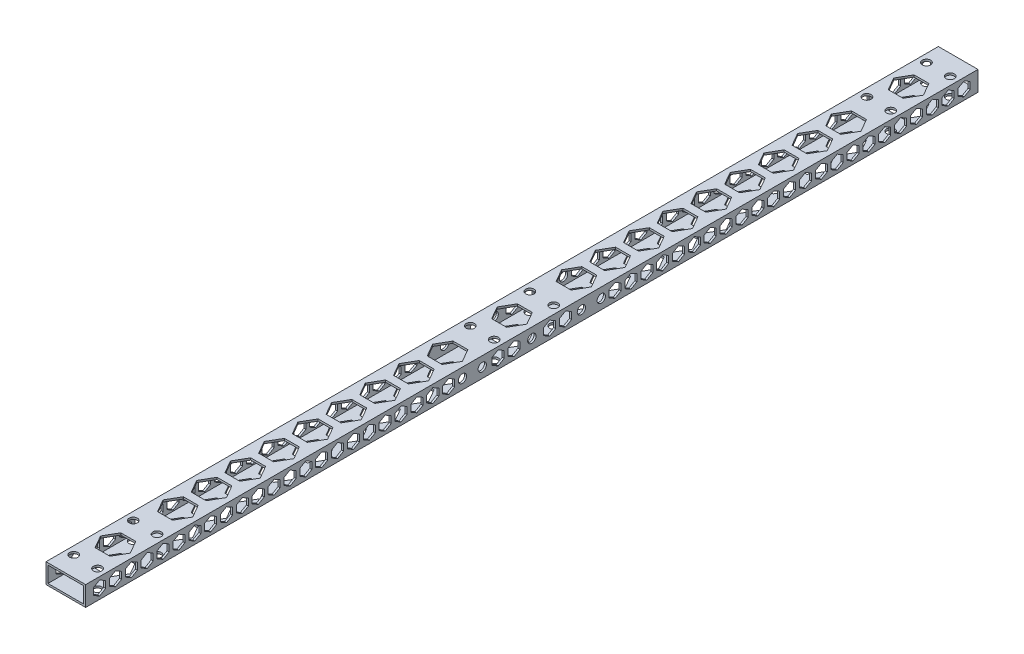
SolidWorks part; units mm, degrees
ref_plane "前视基准面" through (0, 0, 0) normal (0, 0, 1) x (1, 0, 0)
ref_plane "上视基准面" through (0, 0, 0) normal (0, 1, 0) x (1, 0, 0)
ref_plane "右视基准面" through (0, 0, 0) normal (1, 0, 0) x (0, 0, -1)
other "Configuration Table"
sketch "草图1" plane through (0, 0, 0) normal (0, 0, 1) x (1, 0, 0)
  line L1 (0, 0) -> (20, 0)
  line L2 (0, 0) -> (0, -10)
  line L3 (0, -10) -> (20, -10)
  line L4 (20, 0) -> (20, -10)
  dimension "D1" = 10
  dimension "D2" = 20
extrude "拉伸-薄壁1" add sketch "草图1" along normal blind 450 thin
sketch "草图2" plane through (0, 0, 0) normal (0, 1, 0) x (1, 0, 0)
  line L0 (20, -225) -> (0, -225) construction
  line L1 (20, -450) -> (20, 0) construction
  line L2 (0, -450) -> (0, 0) construction
  line L3 (10, 0) -> (10, -450) construction
  line L4 (20, 0) -> (0, 0) construction
  line L5 (20, -450) -> (0, -450) construction
  line L6 (20, -25) -> (0, -25) construction
  line L7 (20, -425) -> (0, -425) construction
  line L8 (13.75, -67) -> (6.25, -67)
  line L9 (13.75, -50) -> (6.25, -50)
  line L10 (6.25, -50) -> (2.5, -56.4952)
  line L11 (2.5, -56.4952) -> (6.25, -62.9904)
  line L12 (6.25, -62.9904) -> (13.75, -62.9904)
  line L13 (13.75, -62.9904) -> (17.5, -56.4952)
  line L14 (17.5, -56.4952) -> (13.75, -50)
  line L15 (17.5, -73.4952) -> (13.75, -67)
  line L16 (13.75, -79.9904) -> (17.5, -73.4952)
  line L17 (6.25, -79.9904) -> (13.75, -79.9904)
  line L18 (2.5, -73.4952) -> (6.25, -79.9904)
  line L19 (6.25, -67) -> (2.5, -73.4952)
  line L20 (13.75, -84) -> (6.25, -84)
  line L21 (17.5, -90.4952) -> (13.75, -84)
  line L22 (13.75, -96.9904) -> (17.5, -90.4952)
  line L23 (6.25, -96.9904) -> (13.75, -96.9904)
  line L24 (2.5, -90.4952) -> (6.25, -96.9904)
  line L25 (6.25, -84) -> (2.5, -90.4952)
  line L26 (13.75, -101) -> (6.25, -101)
  line L27 (17.5, -107.4952) -> (13.75, -101)
  line L28 (13.75, -113.9904) -> (17.5, -107.4952)
  line L29 (6.25, -113.9904) -> (13.75, -113.9904)
  line L30 (2.5, -107.4952) -> (6.25, -113.9904)
  line L31 (6.25, -101) -> (2.5, -107.4952)
  line L32 (13.75, -118) -> (6.25, -118)
  line L33 (17.5, -124.4952) -> (13.75, -118)
  line L34 (13.75, -130.9904) -> (17.5, -124.4952)
  line L35 (6.25, -130.9904) -> (13.75, -130.9904)
  line L36 (2.5, -124.4952) -> (6.25, -130.9904)
  line L37 (6.25, -118) -> (2.5, -124.4952)
  line L38 (13.75, -135) -> (6.25, -135)
  line L39 (17.5, -141.4952) -> (13.75, -135)
  line L40 (13.75, -147.9904) -> (17.5, -141.4952)
  line L41 (6.25, -147.9904) -> (13.75, -147.9904)
  line L42 (2.5, -141.4952) -> (6.25, -147.9904)
  line L43 (6.25, -135) -> (2.5, -141.4952)
  line L44 (13.75, -152) -> (6.25, -152)
  line L45 (17.5, -158.4952) -> (13.75, -152)
  line L46 (13.75, -164.9904) -> (17.5, -158.4952)
  line L47 (6.25, -164.9904) -> (13.75, -164.9904)
  line L48 (2.5, -158.4952) -> (6.25, -164.9904)
  line L49 (6.25, -152) -> (2.5, -158.4952)
  line L50 (13.75, -169) -> (6.25, -169)
  line L51 (17.5, -175.4952) -> (13.75, -169)
  line L52 (13.75, -181.9904) -> (17.5, -175.4952)
  line L53 (6.25, -181.9904) -> (13.75, -181.9904)
  line L54 (2.5, -175.4952) -> (6.25, -181.9904)
  line L55 (6.25, -169) -> (2.5, -175.4952)
  line L56 (13.75, -186) -> (6.25, -186)
  line L57 (17.5, -192.4952) -> (13.75, -186)
  line L58 (13.75, -198.9904) -> (17.5, -192.4952)
  line L59 (6.25, -198.9904) -> (13.75, -198.9904)
  line L60 (2.5, -192.4952) -> (6.25, -198.9904)
  line L61 (6.25, -186) -> (2.5, -192.4952)
  line L62 (6.25, -251.0096) -> (13.75, -251.0096)
  line L63 (13.75, -251.0096) -> (17.5, -257.5048)
  line L64 (2.5, -257.5048) -> (6.25, -251.0096)
  line L65 (6.25, -264) -> (2.5, -257.5048)
  line L66 (17.5, -257.5048) -> (13.75, -264)
  line L67 (13.75, -264) -> (6.25, -264)
  line L68 (6.25, -281) -> (2.5, -274.5048)
  line L69 (2.5, -274.5048) -> (6.25, -268.0096)
  line L70 (6.25, -268.0096) -> (13.75, -268.0096)
  line L71 (13.75, -268.0096) -> (17.5, -274.5048)
  line L72 (17.5, -274.5048) -> (13.75, -281)
  line L73 (13.75, -281) -> (6.25, -281)
  line L74 (6.25, -298) -> (2.5, -291.5048)
  line L75 (2.5, -291.5048) -> (6.25, -285.0096)
  line L76 (6.25, -285.0096) -> (13.75, -285.0096)
  line L77 (13.75, -285.0096) -> (17.5, -291.5048)
  line L78 (17.5, -291.5048) -> (13.75, -298)
  line L79 (13.75, -298) -> (6.25, -298)
  line L80 (6.25, -315) -> (2.5, -308.5048)
  line L81 (2.5, -308.5048) -> (6.25, -302.0096)
  line L82 (6.25, -302.0096) -> (13.75, -302.0096)
  line L83 (13.75, -302.0096) -> (17.5, -308.5048)
  line L84 (17.5, -308.5048) -> (13.75, -315)
  line L85 (13.75, -315) -> (6.25, -315)
  line L86 (6.25, -332) -> (2.5, -325.5048)
  line L87 (2.5, -325.5048) -> (6.25, -319.0096)
  line L88 (6.25, -319.0096) -> (13.75, -319.0096)
  line L89 (13.75, -319.0096) -> (17.5, -325.5048)
  line L90 (17.5, -325.5048) -> (13.75, -332)
  line L91 (13.75, -332) -> (6.25, -332)
  line L92 (6.25, -349) -> (2.5, -342.5048)
  line L93 (2.5, -342.5048) -> (6.25, -336.0096)
  line L94 (6.25, -336.0096) -> (13.75, -336.0096)
  line L95 (13.75, -336.0096) -> (17.5, -342.5048)
  line L96 (17.5, -342.5048) -> (13.75, -349)
  line L97 (13.75, -349) -> (6.25, -349)
  line L98 (6.25, -366) -> (2.5, -359.5048)
  line L99 (2.5, -359.5048) -> (6.25, -353.0096)
  line L100 (6.25, -353.0096) -> (13.75, -353.0096)
  line L101 (13.75, -353.0096) -> (17.5, -359.5048)
  line L102 (17.5, -359.5048) -> (13.75, -366)
  line L103 (13.75, -366) -> (6.25, -366)
  line L104 (6.25, -383) -> (2.5, -376.5048)
  line L105 (2.5, -376.5048) -> (6.25, -370.0096)
  line L106 (6.25, -370.0096) -> (13.75, -370.0096)
  line L107 (13.75, -370.0096) -> (17.5, -376.5048)
  line L108 (17.5, -376.5048) -> (13.75, -383)
  line L109 (17.5, -393.5048) -> (13.75, -400)
  line L110 (13.75, -387.0096) -> (17.5, -393.5048)
  line L111 (6.25, -387.0096) -> (13.75, -387.0096)
  line L112 (2.5, -393.5048) -> (6.25, -387.0096)
  line L113 (6.25, -400) -> (2.5, -393.5048)
  line L114 (13.75, -400) -> (6.25, -400)
  line L115 (13.75, -383) -> (6.25, -383)
  line L116 (20, -25) -> (0, -25) construction
  line L117 (2.5, -425) -> (6.25, -431.4952)
  line L118 (6.25, -431.4952) -> (13.75, -431.4952)
  line L119 (13.75, -431.4952) -> (17.5, -425)
  line L120 (17.5, -425) -> (13.75, -418.5048)
  line L121 (13.75, -418.5048) -> (6.25, -418.5048)
  line L122 (6.25, -418.5048) -> (2.5, -425)
  line L123 (6.25, -31.4952) -> (2.5, -25)
  line L124 (13.75, -31.4952) -> (6.25, -31.4952)
  line L125 (17.5, -25) -> (13.75, -31.4952)
  line L126 (13.75, -18.5048) -> (17.5, -25)
  line L127 (6.25, -18.5048) -> (13.75, -18.5048)
  line L128 (2.5, -25) -> (6.25, -18.5048)
  line L130 (2.5, -225) -> (6.25, -231.4952)
  line L131 (6.25, -231.4952) -> (13.75, -231.4952)
  line L132 (13.75, -231.4952) -> (17.5, -225)
  line L133 (17.5, -225) -> (13.75, -218.5048)
  line L134 (13.75, -218.5048) -> (6.25, -218.5048)
  line L135 (6.25, -218.5048) -> (2.5, -225)
  circle A0 centre (4, -210) radius 2.1
  circle A1 centre (16, -210) radius 2.1
  circle A2 centre (16, -240) radius 2.1
  circle A3 centre (4, -240) radius 2.1
  circle A4 centre (4, -10) radius 2.1
  circle A5 centre (16, -10) radius 2.1
  circle A6 centre (16, -40) radius 2.1
  circle A7 centre (4, -40) radius 2.1
  circle A8 centre (4, -410) radius 2.1
  circle A9 centre (16, -410) radius 2.1
  circle A10 centre (16, -440) radius 2.1
  circle A11 centre (4, -440) radius 2.1
  circle A12 centre (10, -56.4952) radius 6.4952 construction
  circle A13 centre (10, -393.5048) radius 6.4952 construction
  circle A14 centre (10, -425) radius 6.4952 construction
  circle A15 centre (10, -25) radius 6.4952 construction
  circle A16 centre (10, -225) radius 6.4952 construction
  point P153 (2.5, -225)
  dimension "D1" = 4.2
  dimension "D5" = 4.2
  dimension "D2" = 6
  dimension "D3" = 15
  dimension "D4" = 200
  dimension "D6" = 6
  dimension "D7" = 15
  dimension "D8" = 7.5
  dimension "D9" = 10
  dimension "D11" = 17
  dimension "D12" = 7.5
  dimension "D13" = 7.5
  dimension "D10" = 9
extrude "切除-拉伸1" cut sketch "草图2" against normal through all
sketch "草图3" plane through (20, 0, 0) normal (1, 0, 0) x (0, 0, -1)
  line L0 (-225, 0) -> (-225, -10) construction
  line L1 (-450, 0) -> (0, 0) construction
  line L2 (-450, -10) -> (0, -10) construction
  line L3 (-225, -5) -> (-450, -5) construction
  line L4 (-450, -10) -> (-450, 0) construction
  line L5 (-434.9689, -1.5) -> (-438, -3.25)
  line L6 (-442.9689, -1.5) -> (-446, -3.25)
  line L7 (-446, -3.25) -> (-446, -6.75)
  line L8 (-446, -6.75) -> (-442.9689, -8.5)
  line L9 (-442.9689, -8.5) -> (-439.9378, -6.75)
  line L10 (-439.9378, -6.75) -> (-439.9378, -3.25)
  line L11 (-439.9378, -3.25) -> (-442.9689, -1.5)
  line L12 (-431.9378, -3.25) -> (-434.9689, -1.5)
  line L13 (-438, -3.25) -> (-438, -6.75)
  line L14 (-431.9378, -6.75) -> (-431.9378, -3.25)
  line L15 (-434.9689, -8.5) -> (-431.9378, -6.75)
  line L16 (-438, -6.75) -> (-434.9689, -8.5)
  line L17 (-426.9689, -1.5) -> (-430, -3.25)
  line L18 (-423.9378, -3.25) -> (-426.9689, -1.5)
  line L19 (-430, -3.25) -> (-430, -6.75)
  line L20 (-423.9378, -6.75) -> (-423.9378, -3.25)
  line L21 (-426.9689, -8.5) -> (-423.9378, -6.75)
  line L22 (-430, -6.75) -> (-426.9689, -8.5)
  line L23 (-418.9689, -1.5) -> (-422, -3.25)
  line L24 (-415.9378, -3.25) -> (-418.9689, -1.5)
  line L25 (-422, -3.25) -> (-422, -6.75)
  line L26 (-415.9378, -6.75) -> (-415.9378, -3.25)
  line L27 (-418.9689, -8.5) -> (-415.9378, -6.75)
  line L28 (-422, -6.75) -> (-418.9689, -8.5)
  line L29 (-410.9689, -1.5) -> (-414, -3.25)
  line L30 (-407.9378, -3.25) -> (-410.9689, -1.5)
  line L31 (-414, -3.25) -> (-414, -6.75)
  line L32 (-407.9378, -6.75) -> (-407.9378, -3.25)
  line L33 (-410.9689, -8.5) -> (-407.9378, -6.75)
  line L34 (-414, -6.75) -> (-410.9689, -8.5)
  line L35 (-402.9689, -1.5) -> (-406, -3.25)
  line L36 (-399.9378, -3.25) -> (-402.9689, -1.5)
  line L37 (-406, -3.25) -> (-406, -6.75)
  line L38 (-399.9378, -6.75) -> (-399.9378, -3.25)
  line L39 (-402.9689, -8.5) -> (-399.9378, -6.75)
  line L40 (-406, -6.75) -> (-402.9689, -8.5)
  line L41 (-394.9689, -1.5) -> (-398, -3.25)
  line L42 (-391.9378, -3.25) -> (-394.9689, -1.5)
  line L43 (-398, -3.25) -> (-398, -6.75)
  line L44 (-391.9378, -6.75) -> (-391.9378, -3.25)
  line L45 (-394.9689, -8.5) -> (-391.9378, -6.75)
  line L46 (-398, -6.75) -> (-394.9689, -8.5)
  line L47 (-386.9689, -1.5) -> (-390, -3.25)
  line L48 (-383.9378, -3.25) -> (-386.9689, -1.5)
  line L49 (-390, -3.25) -> (-390, -6.75)
  line L50 (-383.9378, -6.75) -> (-383.9378, -3.25)
  line L51 (-386.9689, -8.5) -> (-383.9378, -6.75)
  line L52 (-390, -6.75) -> (-386.9689, -8.5)
  line L53 (-378.9689, -1.5) -> (-382, -3.25)
  line L54 (-375.9378, -3.25) -> (-378.9689, -1.5)
  line L55 (-382, -3.25) -> (-382, -6.75)
  line L56 (-375.9378, -6.75) -> (-375.9378, -3.25)
  line L57 (-378.9689, -8.5) -> (-375.9378, -6.75)
  line L58 (-382, -6.75) -> (-378.9689, -8.5)
  line L59 (-370.9689, -1.5) -> (-374, -3.25)
  line L60 (-367.9378, -3.25) -> (-370.9689, -1.5)
  line L61 (-374, -3.25) -> (-374, -6.75)
  line L62 (-367.9378, -6.75) -> (-367.9378, -3.25)
  line L63 (-370.9689, -8.5) -> (-367.9378, -6.75)
  line L64 (-374, -6.75) -> (-370.9689, -8.5)
  line L65 (-362.9689, -1.5) -> (-366, -3.25)
  line L66 (-359.9378, -3.25) -> (-362.9689, -1.5)
  line L67 (-366, -3.25) -> (-366, -6.75)
  line L68 (-359.9378, -6.75) -> (-359.9378, -3.25)
  line L69 (-362.9689, -8.5) -> (-359.9378, -6.75)
  line L70 (-366, -6.75) -> (-362.9689, -8.5)
  line L71 (-354.9689, -1.5) -> (-358, -3.25)
  line L72 (-351.9378, -3.25) -> (-354.9689, -1.5)
  line L73 (-358, -3.25) -> (-358, -6.75)
  line L74 (-351.9378, -6.75) -> (-351.9378, -3.25)
  line L75 (-354.9689, -8.5) -> (-351.9378, -6.75)
  line L76 (-358, -6.75) -> (-354.9689, -8.5)
  line L77 (-346.9689, -1.5) -> (-350, -3.25)
  line L78 (-343.9378, -3.25) -> (-346.9689, -1.5)
  line L79 (-350, -3.25) -> (-350, -6.75)
  line L80 (-343.9378, -6.75) -> (-343.9378, -3.25)
  line L81 (-346.9689, -8.5) -> (-343.9378, -6.75)
  line L82 (-350, -6.75) -> (-346.9689, -8.5)
  line L83 (-338.9689, -1.5) -> (-342, -3.25)
  line L84 (-335.9378, -3.25) -> (-338.9689, -1.5)
  line L85 (-342, -3.25) -> (-342, -6.75)
  line L86 (-335.9378, -6.75) -> (-335.9378, -3.25)
  line L87 (-338.9689, -8.5) -> (-335.9378, -6.75)
  line L88 (-342, -6.75) -> (-338.9689, -8.5)
  line L89 (-330.9689, -1.5) -> (-334, -3.25)
  line L90 (-327.9378, -3.25) -> (-330.9689, -1.5)
  line L91 (-334, -3.25) -> (-334, -6.75)
  line L92 (-327.9378, -6.75) -> (-327.9378, -3.25)
  line L93 (-330.9689, -8.5) -> (-327.9378, -6.75)
  line L94 (-334, -6.75) -> (-330.9689, -8.5)
  line L95 (-322.9689, -1.5) -> (-326, -3.25)
  line L96 (-319.9378, -3.25) -> (-322.9689, -1.5)
  line L97 (-326, -3.25) -> (-326, -6.75)
  line L98 (-319.9378, -6.75) -> (-319.9378, -3.25)
  line L99 (-322.9689, -8.5) -> (-319.9378, -6.75)
  line L100 (-326, -6.75) -> (-322.9689, -8.5)
  line L101 (-314.9689, -1.5) -> (-318, -3.25)
  line L102 (-311.9378, -3.25) -> (-314.9689, -1.5)
  line L103 (-318, -3.25) -> (-318, -6.75)
  line L104 (-311.9378, -6.75) -> (-311.9378, -3.25)
  line L105 (-314.9689, -8.5) -> (-311.9378, -6.75)
  line L106 (-318, -6.75) -> (-314.9689, -8.5)
  line L107 (-306.9689, -1.5) -> (-310, -3.25)
  line L108 (-303.9378, -3.25) -> (-306.9689, -1.5)
  line L109 (-310, -3.25) -> (-310, -6.75)
  line L110 (-303.9378, -6.75) -> (-303.9378, -3.25)
  line L111 (-306.9689, -8.5) -> (-303.9378, -6.75)
  line L112 (-310, -6.75) -> (-306.9689, -8.5)
  line L113 (-298.9689, -1.5) -> (-302, -3.25)
  line L114 (-295.9378, -3.25) -> (-298.9689, -1.5)
  line L115 (-302, -3.25) -> (-302, -6.75)
  line L116 (-295.9378, -6.75) -> (-295.9378, -3.25)
  line L117 (-298.9689, -8.5) -> (-295.9378, -6.75)
  line L118 (-302, -6.75) -> (-298.9689, -8.5)
  line L119 (-290.9689, -1.5) -> (-294, -3.25)
  line L120 (-287.9378, -3.25) -> (-290.9689, -1.5)
  line L121 (-294, -3.25) -> (-294, -6.75)
  line L122 (-287.9378, -6.75) -> (-287.9378, -3.25)
  line L123 (-290.9689, -8.5) -> (-287.9378, -6.75)
  line L124 (-294, -6.75) -> (-290.9689, -8.5)
  line L125 (-282.9689, -1.5) -> (-286, -3.25)
  line L126 (-279.9378, -3.25) -> (-282.9689, -1.5)
  line L127 (-286, -3.25) -> (-286, -6.75)
  line L128 (-279.9378, -6.75) -> (-279.9378, -3.25)
  line L129 (-282.9689, -8.5) -> (-279.9378, -6.75)
  line L130 (-286, -6.75) -> (-282.9689, -8.5)
  line L131 (-274.9689, -1.5) -> (-278, -3.25)
  line L132 (-271.9378, -3.25) -> (-274.9689, -1.5)
  line L133 (-278, -3.25) -> (-278, -6.75)
  line L134 (-271.9378, -6.75) -> (-271.9378, -3.25)
  line L135 (-274.9689, -8.5) -> (-271.9378, -6.75)
  line L136 (-278, -6.75) -> (-274.9689, -8.5)
  line L137 (-266.9689, -1.5) -> (-270, -3.25)
  line L138 (-263.9378, -3.25) -> (-266.9689, -1.5)
  line L139 (-270, -3.25) -> (-270, -6.75)
  line L140 (-263.9378, -6.75) -> (-263.9378, -3.25)
  line L141 (-266.9689, -8.5) -> (-263.9378, -6.75)
  line L142 (-270, -6.75) -> (-266.9689, -8.5)
  line L143 (-180, -6.75) -> (-183.0311, -8.5)
  line L144 (-183.0311, -8.5) -> (-186.0622, -6.75)
  line L145 (-186.0622, -6.75) -> (-186.0622, -3.25)
  line L146 (-180, -3.25) -> (-180, -6.75)
  line L147 (-186.0622, -3.25) -> (-183.0311, -1.5)
  line L148 (-183.0311, -1.5) -> (-180, -3.25)
  line L149 (-172, -6.75) -> (-175.0311, -8.5)
  line L150 (-175.0311, -8.5) -> (-178.0622, -6.75)
  line L151 (-178.0622, -6.75) -> (-178.0622, -3.25)
  line L152 (-172, -3.25) -> (-172, -6.75)
  line L153 (-178.0622, -3.25) -> (-175.0311, -1.5)
  line L154 (-175.0311, -1.5) -> (-172, -3.25)
  line L155 (-164, -6.75) -> (-167.0311, -8.5)
  line L156 (-167.0311, -8.5) -> (-170.0622, -6.75)
  line L157 (-170.0622, -6.75) -> (-170.0622, -3.25)
  line L158 (-164, -3.25) -> (-164, -6.75)
  line L159 (-170.0622, -3.25) -> (-167.0311, -1.5)
  line L160 (-167.0311, -1.5) -> (-164, -3.25)
  line L161 (-156, -6.75) -> (-159.0311, -8.5)
  line L162 (-159.0311, -8.5) -> (-162.0622, -6.75)
  line L163 (-162.0622, -6.75) -> (-162.0622, -3.25)
  line L164 (-156, -3.25) -> (-156, -6.75)
  line L165 (-162.0622, -3.25) -> (-159.0311, -1.5)
  line L166 (-159.0311, -1.5) -> (-156, -3.25)
  line L167 (-148, -6.75) -> (-151.0311, -8.5)
  line L168 (-151.0311, -8.5) -> (-154.0622, -6.75)
  line L169 (-154.0622, -6.75) -> (-154.0622, -3.25)
  line L170 (-148, -3.25) -> (-148, -6.75)
  line L171 (-154.0622, -3.25) -> (-151.0311, -1.5)
  line L172 (-151.0311, -1.5) -> (-148, -3.25)
  line L173 (-140, -6.75) -> (-143.0311, -8.5)
  line L174 (-143.0311, -8.5) -> (-146.0622, -6.75)
  line L175 (-146.0622, -6.75) -> (-146.0622, -3.25)
  line L176 (-140, -3.25) -> (-140, -6.75)
  line L177 (-146.0622, -3.25) -> (-143.0311, -1.5)
  line L178 (-143.0311, -1.5) -> (-140, -3.25)
  line L179 (-132, -6.75) -> (-135.0311, -8.5)
  line L180 (-135.0311, -8.5) -> (-138.0622, -6.75)
  line L181 (-138.0622, -6.75) -> (-138.0622, -3.25)
  line L182 (-132, -3.25) -> (-132, -6.75)
  line L183 (-138.0622, -3.25) -> (-135.0311, -1.5)
  line L184 (-135.0311, -1.5) -> (-132, -3.25)
  line L185 (-124, -6.75) -> (-127.0311, -8.5)
  line L186 (-127.0311, -8.5) -> (-130.0622, -6.75)
  line L187 (-130.0622, -6.75) -> (-130.0622, -3.25)
  line L188 (-124, -3.25) -> (-124, -6.75)
  line L189 (-130.0622, -3.25) -> (-127.0311, -1.5)
  line L190 (-127.0311, -1.5) -> (-124, -3.25)
  line L191 (-116, -6.75) -> (-119.0311, -8.5)
  line L192 (-119.0311, -8.5) -> (-122.0622, -6.75)
  line L193 (-122.0622, -6.75) -> (-122.0622, -3.25)
  line L194 (-116, -3.25) -> (-116, -6.75)
  line L195 (-122.0622, -3.25) -> (-119.0311, -1.5)
  line L196 (-119.0311, -1.5) -> (-116, -3.25)
  line L197 (-108, -6.75) -> (-111.0311, -8.5)
  line L198 (-111.0311, -8.5) -> (-114.0622, -6.75)
  line L199 (-114.0622, -6.75) -> (-114.0622, -3.25)
  line L200 (-108, -3.25) -> (-108, -6.75)
  line L201 (-114.0622, -3.25) -> (-111.0311, -1.5)
  line L202 (-111.0311, -1.5) -> (-108, -3.25)
  line L203 (-100, -6.75) -> (-103.0311, -8.5)
  line L204 (-103.0311, -8.5) -> (-106.0622, -6.75)
  line L205 (-106.0622, -6.75) -> (-106.0622, -3.25)
  line L206 (-100, -3.25) -> (-100, -6.75)
  line L207 (-106.0622, -3.25) -> (-103.0311, -1.5)
  line L208 (-103.0311, -1.5) -> (-100, -3.25)
  line L209 (-92, -6.75) -> (-95.0311, -8.5)
  line L210 (-95.0311, -8.5) -> (-98.0622, -6.75)
  line L211 (-98.0622, -6.75) -> (-98.0622, -3.25)
  line L212 (-92, -3.25) -> (-92, -6.75)
  line L213 (-98.0622, -3.25) -> (-95.0311, -1.5)
  line L214 (-95.0311, -1.5) -> (-92, -3.25)
  line L215 (-84, -6.75) -> (-87.0311, -8.5)
  line L216 (-87.0311, -8.5) -> (-90.0622, -6.75)
  line L217 (-90.0622, -6.75) -> (-90.0622, -3.25)
  line L218 (-84, -3.25) -> (-84, -6.75)
  line L219 (-90.0622, -3.25) -> (-87.0311, -1.5)
  line L220 (-87.0311, -1.5) -> (-84, -3.25)
  line L221 (-76, -6.75) -> (-79.0311, -8.5)
  line L222 (-79.0311, -8.5) -> (-82.0622, -6.75)
  line L223 (-82.0622, -6.75) -> (-82.0622, -3.25)
  line L224 (-76, -3.25) -> (-76, -6.75)
  line L225 (-82.0622, -3.25) -> (-79.0311, -1.5)
  line L226 (-79.0311, -1.5) -> (-76, -3.25)
  line L227 (-68, -6.75) -> (-71.0311, -8.5)
  line L228 (-71.0311, -8.5) -> (-74.0622, -6.75)
  line L229 (-74.0622, -6.75) -> (-74.0622, -3.25)
  line L230 (-68, -3.25) -> (-68, -6.75)
  line L231 (-74.0622, -3.25) -> (-71.0311, -1.5)
  line L232 (-71.0311, -1.5) -> (-68, -3.25)
  line L233 (-60, -6.75) -> (-63.0311, -8.5)
  line L234 (-63.0311, -8.5) -> (-66.0622, -6.75)
  line L235 (-66.0622, -6.75) -> (-66.0622, -3.25)
  line L236 (-60, -3.25) -> (-60, -6.75)
  line L237 (-66.0622, -3.25) -> (-63.0311, -1.5)
  line L238 (-63.0311, -1.5) -> (-60, -3.25)
  line L239 (-52, -6.75) -> (-55.0311, -8.5)
  line L240 (-55.0311, -8.5) -> (-58.0622, -6.75)
  line L241 (-58.0622, -6.75) -> (-58.0622, -3.25)
  line L242 (-52, -3.25) -> (-52, -6.75)
  line L243 (-58.0622, -3.25) -> (-55.0311, -1.5)
  line L244 (-55.0311, -1.5) -> (-52, -3.25)
  line L245 (-44, -6.75) -> (-47.0311, -8.5)
  line L246 (-47.0311, -8.5) -> (-50.0622, -6.75)
  line L247 (-50.0622, -6.75) -> (-50.0622, -3.25)
  line L248 (-44, -3.25) -> (-44, -6.75)
  line L249 (-50.0622, -3.25) -> (-47.0311, -1.5)
  line L250 (-47.0311, -1.5) -> (-44, -3.25)
  line L251 (-36, -6.75) -> (-39.0311, -8.5)
  line L252 (-39.0311, -8.5) -> (-42.0622, -6.75)
  line L253 (-42.0622, -6.75) -> (-42.0622, -3.25)
  line L254 (-36, -3.25) -> (-36, -6.75)
  line L255 (-42.0622, -3.25) -> (-39.0311, -1.5)
  line L256 (-39.0311, -1.5) -> (-36, -3.25)
  line L257 (-28, -6.75) -> (-31.0311, -8.5)
  line L258 (-31.0311, -8.5) -> (-34.0622, -6.75)
  line L259 (-34.0622, -6.75) -> (-34.0622, -3.25)
  line L260 (-28, -3.25) -> (-28, -6.75)
  line L261 (-34.0622, -3.25) -> (-31.0311, -1.5)
  line L262 (-31.0311, -1.5) -> (-28, -3.25)
  line L263 (-20, -6.75) -> (-23.0311, -8.5)
  line L264 (-23.0311, -8.5) -> (-26.0622, -6.75)
  line L265 (-26.0622, -6.75) -> (-26.0622, -3.25)
  line L266 (-20, -3.25) -> (-20, -6.75)
  line L267 (-26.0622, -3.25) -> (-23.0311, -1.5)
  line L268 (-23.0311, -1.5) -> (-20, -3.25)
  line L269 (-12, -6.75) -> (-15.0311, -8.5)
  line L270 (-15.0311, -8.5) -> (-18.0622, -6.75)
  line L271 (-18.0622, -6.75) -> (-18.0622, -3.25)
  line L272 (-12, -3.25) -> (-12, -6.75)
  line L273 (-18.0622, -3.25) -> (-15.0311, -1.5)
  line L274 (-10.0622, -3.25) -> (-7.0311, -1.5)
  line L275 (-10.0622, -6.75) -> (-10.0622, -3.25)
  line L276 (-7.0311, -8.5) -> (-10.0622, -6.75)
  line L277 (-4, -6.75) -> (-7.0311, -8.5)
  line L278 (-4, -3.25) -> (-4, -6.75)
  line L279 (-7.0311, -1.5) -> (-4, -3.25)
  line L280 (-15.0311, -1.5) -> (-12, -3.25)
  line L281 (-234, -1.5) -> (-237.0311, -3.25)
  line L282 (-242, -1.5) -> (-245.0311, -3.25)
  line L283 (-245.0311, -3.25) -> (-245.0311, -6.75)
  line L284 (-245.0311, -6.75) -> (-242, -8.5)
  line L285 (-242, -8.5) -> (-238.9689, -6.75)
  line L286 (-238.9689, -6.75) -> (-238.9689, -3.25)
  line L287 (-238.9689, -3.25) -> (-242, -1.5)
  line L288 (-230.9689, -3.25) -> (-234, -1.5)
  line L289 (-237.0311, -3.25) -> (-237.0311, -6.75)
  line L290 (-237.0311, -6.75) -> (-234, -8.5)
  line L291 (-234, -8.5) -> (-230.9689, -6.75)
  line L292 (-230.9689, -6.75) -> (-230.9689, -3.25)
  line L293 (-219.0311, -6.75) -> (-219.0311, -3.25)
  line L294 (-216, -8.5) -> (-219.0311, -6.75)
  line L295 (-212.9689, -6.75) -> (-216, -8.5)
  line L296 (-212.9689, -3.25) -> (-212.9689, -6.75)
  line L297 (-219.0311, -3.25) -> (-216, -1.5)
  line L298 (-211.0311, -3.25) -> (-208, -1.5)
  line L299 (-211.0311, -6.75) -> (-211.0311, -3.25)
  line L300 (-208, -8.5) -> (-211.0311, -6.75)
  line L301 (-204.9689, -6.75) -> (-208, -8.5)
  line L302 (-204.9689, -3.25) -> (-204.9689, -6.75)
  line L303 (-208, -1.5) -> (-204.9689, -3.25)
  line L304 (-216, -1.5) -> (-212.9689, -3.25)
  circle A0 centre (-250, -5) radius 2.1
  circle A1 centre (-260, -5) radius 2.1
  circle A2 centre (-190, -5) radius 2.1
  circle A3 centre (-200, -5) radius 2.1
  circle A4 centre (-225, -5) radius 2.1
  circle A5 centre (-442.9689, -5) radius 3.0311 construction
  circle A6 centre (-7.0311, -5) radius 3.0311 construction
  circle A7 centre (-242, -5) radius 3.0311 construction
  circle A8 centre (-208, -5) radius 3.0311 construction
  point P300 (0, 0)
  dimension "D1" = 25
  dimension "D2" = 4.2
  dimension "D3" = 4.2
  dimension "D5" = 4.2
  dimension "D4" = 10
  dimension "D6" = 3.5
  dimension "D7" = 4
  dimension "D9" = 8
  dimension "D10" = 3.5
  dimension "D11" = 8
  dimension "D13" = 8
  dimension "D8" = 23
  dimension "D12" = 2
extrude "切除-拉伸2" cut sketch "草图3" against normal through all
